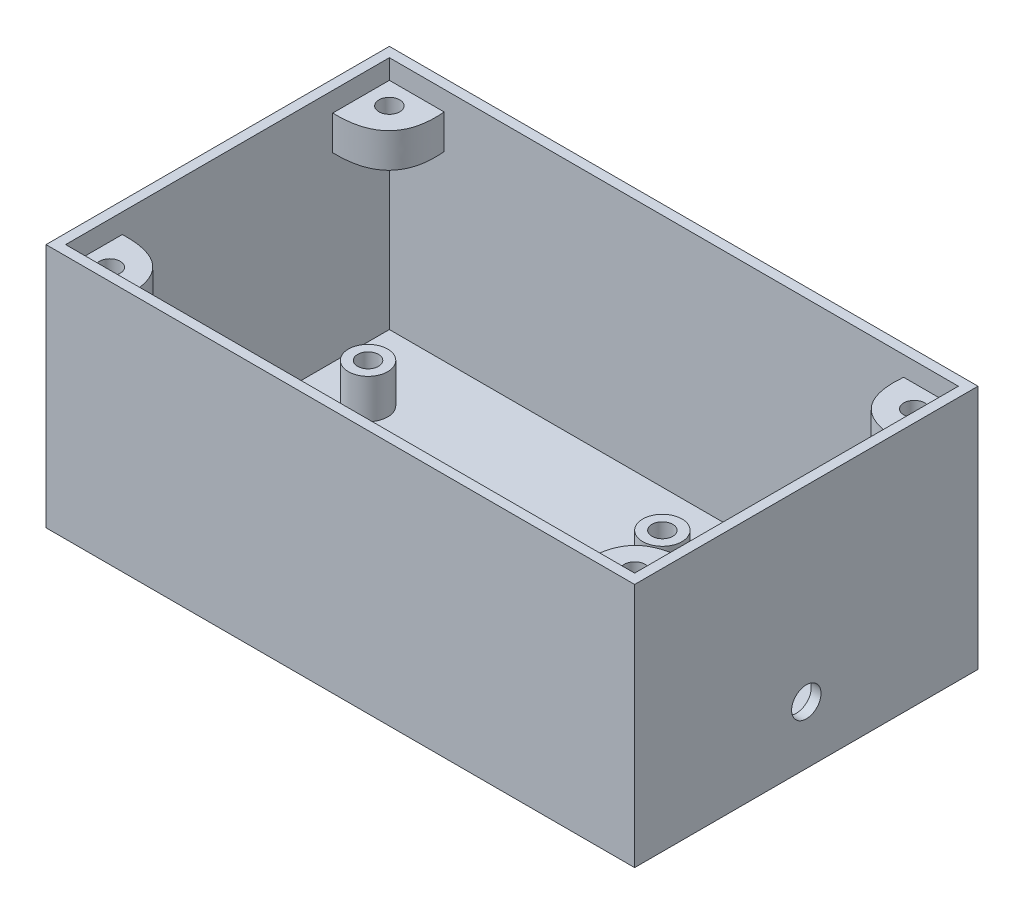
SolidWorks part; units mm, degrees
ref_plane "Front Plane" through (0, 0, 0) normal (0, 0, 1) x (1, 0, 0)
ref_plane "Top Plane" through (0, 0, 0) normal (0, 1, 0) x (1, 0, 0)
ref_plane "Right Plane" through (0, 0, 0) normal (1, 0, 0) x (0, 0, -1)
sketch "Sketch1" plane through (0, 0, 0) normal (0, 1, 0) x (1, 0, 0)
  line L1 (-60, 35) -> (60, 35)
  line L2 (-60, 35) -> (-60, -35)
  line L3 (-60, -35) -> (60, -35)
  line L4 (60, 35) -> (60, -35)
  line L5 (-60, 35) -> (60, -35) construction
  line L6 (-60, -35) -> (60, 35) construction
  line L7 (-58, 33) -> (58, 33)
  line L8 (-58, 33) -> (-58, -33)
  line L9 (-58, -33) -> (58, -33)
  line L10 (58, 33) -> (58, -33)
  line L11 (-58, 33) -> (58, -33) construction
  line L12 (-58, -33) -> (58, 33) construction
  point P0 (0, 0)
  point P6 (0, 0)
  dimension "D1" = 120
  dimension "D2" = 70
  dimension "D3" = 2
  dimension "D4" = 2
extrude "Boss-Extrude1" add sketch "Sketch1" along normal blind 50 contours L1 L4 L3 L2
sketch "Sketch3" plane through (0, 50, 0) normal (0, 1, 0) x (1, 0, 0)
  line L0 (-60, 35) -> (-60, -35) construction
  line L1 (-60, 35) -> (60, 35) construction
  line L2 (60, 35) -> (60, -35) construction
  line L3 (-60, -35) -> (60, -35) construction
  point P1 (-53.5, 0)
  point P2 (-53.5, -28.5)
  point P3 (0, -28.5)
  point P4 (53.5, -28.5)
  point P5 (53.5, 0)
  point P8 (-53.5, 28.5)
  point P9 (0, 28.5)
  point P10 (53.5, 28.5)
  dimension "D1" = 6.5
  dimension "D2" = 6.5
  dimension "D3" = 6.5
  dimension "D4" = 6.5
sketch "Sketch4" plane through (0, 50, 0) normal (0, 1, 0) x (1, 0, 0)
  line L0 (-60, 35) -> (60, 35) construction
  line L1 (-58, 33) -> (58, 33)
  line L2 (-58, 33) -> (-58, -33)
  line L3 (-58, -33) -> (58, -33)
  line L4 (58, 33) -> (58, -33)
  line L5 (-58, 33) -> (58, -33) construction
  line L6 (-58, -33) -> (58, 33) construction
  line L7 (60, 35) -> (60, -35) construction
  point P0 (0, 0)
  dimension "D1" = 2
  dimension "D2" = 2
extrude "Cut-Extrude1" cut sketch "Sketch4" against normal blind 48
sketch "Sketch5" plane through (0, 2, 0) normal (0, 1, 0) x (1, 0, 0)
  circle A0 centre (-53.5, 28.5) radius 2.125
  circle A2 centre (53.5, 28.5) radius 2.125
  circle A4 centre (53.5, -28.5) radius 2.125
  circle A6 centre (-53.5, -28.5) radius 2.125
  circle A7 centre (-53.5, 28.5) radius 4
  circle A8 centre (-53.5, -28.5) radius 3.8057
  circle A13 centre (53.5, -28.5) radius 4
  circle A15 centre (53.5, 28.5) radius 4
sketch "Sketch7" plane through (0, 2, 0) normal (0, 1, 0) x (1, 0, 0)
  circle A0 centre (-46.7348, 17.3882) radius 2.125
  circle A1 centre (-46.7348, -17.8618) radius 2.125
  circle A2 centre (13.2652, -17.8618) radius 2.125
  circle A3 centre (13.2652, 17.3882) radius 2.125
  circle A4 centre (27.9892, 23.9843) radius 2.125
  circle A5 centre (41.9892, 23.9843) radius 2.125
  circle A6 centre (27.9892, -25.0157) radius 2.125
  circle A7 centre (41.9892, -25.0157) radius 2.125
  circle A8 centre (41.9892, 23.9843) radius 4
  circle A9 centre (27.9892, 23.9843) radius 4
  circle A10 centre (27.9892, -25.0157) radius 4
  circle A11 centre (41.9892, -25.0157) radius 4
  circle A12 centre (13.2652, -17.8618) radius 4
  circle A13 centre (13.2652, 17.3882) radius 4
  circle A14 centre (-46.7348, 17.3882) radius 4
  circle A15 centre (-46.7348, -17.8618) radius 4
  point P0 (-46.7348, 17.3882)
  point P1 (13.2652, 17.3882)
  point P2 (-46.7348, -17.8618)
  point P3 (13.2652, -17.8618)
  point P4 (41.9892, 23.9843)
  point P5 (27.9892, -25.0157)
  point P6 (27.9892, 23.9843)
  point P7 (41.9892, -25.0157)
  dimension "D1" = 60
  dimension "D2" = 14
  dimension "D3" = 35.25
  dimension "D4" = 49
extrude "Boss-Extrude3" add sketch "Sketch7" along normal blind 8
sketch "Sketch9" plane through (60, 0, 0) normal (1, 0, 0) x (0, 0, -1)
  circle A0 centre (0, 11.776) radius 3
sketch "Sketch10" plane through (-60, 0, 0) normal (-1, 0, 0) x (0, 0, 1)
  circle A0 centre (0, 11.776) radius 3
extrude "Cut-Extrude2" cut sketch "Sketch9" against normal blind 3 contours A0
extrude "Cut-Extrude3" cut sketch "Sketch10" against normal blind 3 contours A0
ref_plane "Plane1" through (0, 39, 0) normal (0, 1, 0) x (1, 0, 0)
sketch "Sketch12" plane through (0, 39, 0) normal (0, 1, 0) x (1, 0, 0)
  line L0 (-58, -33) -> (58, -33) construction
  line L1 (58, -33) -> (58, 33) construction
  line L2 (0, -27.5) -> (0, 27.5) construction
  line L3 (-46.8367, -33) -> (-58, -33)
  line L5 (-58, -33) -> (-58, -21.44)
  line L6 (46.8367, -33) -> (58, -33)
  line L7 (58, -33) -> (58, -21.44)
  line L8 (58, 21.44) -> (58, 33)
  line L9 (58, 33) -> (46.8367, 33)
  line L10 (-46.8367, 33) -> (-58, 33)
  line L11 (-58, 33) -> (-58, 21.44)
  spline S0 degree 2 poles (46.8367, -33) (45.7474, -21.0681) (58, -21.44) knots 0 0 0 1 1 1
  spline S1 degree 2 poles (-46.8367, -33) (-45.7474, -21.0681) (-58, -21.44) knots 0 0 0 1 1 1
  spline S2 degree 2 poles (46.8367, 33) (45.7474, 21.0681) (58, 21.44) knots 0 0 0 1 1 1
  spline S3 degree 2 poles (-46.8367, 33) (-45.7474, 21.0681) (-58, 21.44) knots 0 0 0 1 1 1
extrude "Boss-Extrude4" add sketch "Sketch12" along normal blind 7
sketch "Sketch13" plane through (0, 46, 0) normal (0, 1, 0) x (1, 0, 0)
  circle A0 centre (-53.5, -28.5) radius 2.125
  circle A1 centre (-53.5, 28.5) radius 2.125
  circle A2 centre (53.5, -28.5) radius 2.125
  circle A3 centre (53.5, 28.5) radius 2.125
extrude "Cut-Extrude4" cut sketch "Sketch13" against normal blind 5
equation "\"D2@Sketch3\"=\"D1@Sketch3\""
equation "\"D3@Sketch3\"=\"D1@Sketch3\""
equation "\"D4@Sketch3\"=\"D1@Sketch3\""
equation "\"D4@Sketch1\"=\"D3@Sketch1\""
equation "\"D2@Sketch4\"=\"D1@Sketch4\""
